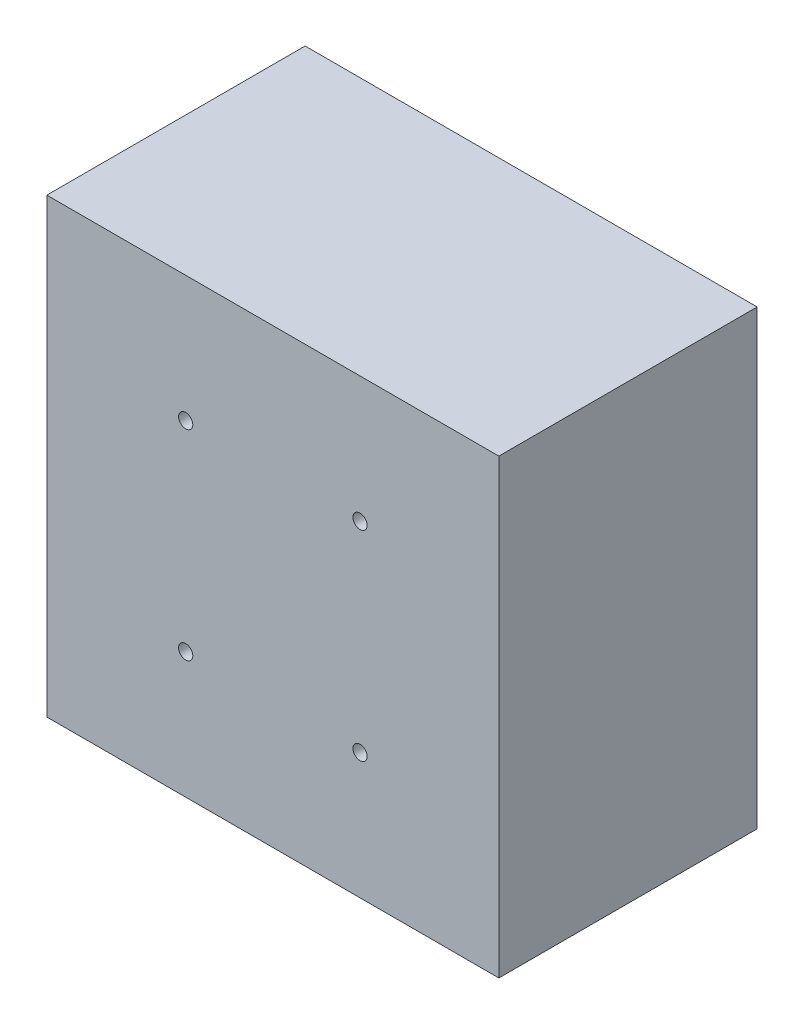
SolidWorks part; units mm, degrees
ref_plane "前视基准面" through (0, 0, 0) normal (0, 0, 1) x (1, 0, 0)
ref_plane "上视基准面" through (0, 0, 0) normal (0, 1, 0) x (1, 0, 0)
ref_plane "右视基准面" through (0, 0, 0) normal (1, 0, 0) x (0, 0, -1)
other "Configuration Table"
sketch "草图1" plane through (0, 0, 0) normal (0, 0, 1) x (1, 0, 0)
  line L1 (0, 0) -> (70, 0)
  line L2 (0, 0) -> (0, 70)
  line L3 (0, 70) -> (70, 70)
  line L4 (70, 0) -> (70, 70)
  dimension "D1" = 70
  dimension "D2" = 70
extrude "凸台-拉伸1" add sketch "草图1" along normal blind 40
sketch "草图2" plane through (0, 0, 40) normal (0, 0, 1) x (1, 0, 0)
  line L0 (70, 70) -> (0, 0)
  line L5 (0, 70) -> (70, 0)
  line L6 (21.5, 50.5) -> (48.5, 50.5) construction
  line L7 (18.25, 16.25) -> (51.75, 16.25) construction
  line L8 (18.25, 16.25) -> (18.25, 53.75) construction
  line L9 (18.25, 53.75) -> (51.75, 53.75) construction
  line L10 (51.75, 16.25) -> (51.75, 53.75) construction
  line L11 (18.25, 16.25) -> (51.75, 53.75) construction
  line L12 (18.25, 53.75) -> (51.75, 16.25) construction
  line L13 (48.5, 19.5) -> (48.5, 50.5) construction
  line L14 (21.5, 19.5) -> (48.5, 19.5) construction
  line L15 (21.5, 19.5) -> (21.5, 50.5) construction
  circle A0 centre (21.5, 50.5) radius 1.1
  circle A1 centre (48.5, 50.5) radius 1.1
  circle A2 centre (48.5, 19.5) radius 1.1
  circle A3 centre (21.5, 19.5) radius 1.1
  point P0 (35, 35)
  dimension "D4" = 2.2
  dimension "D1" = 37.5
  dimension "D2" = 33.5
  dimension "D3" = 3.25
extrude "切除-拉伸1" cut sketch "草图2" against normal blind 20 contours A0 | A1 | A2 | A3
